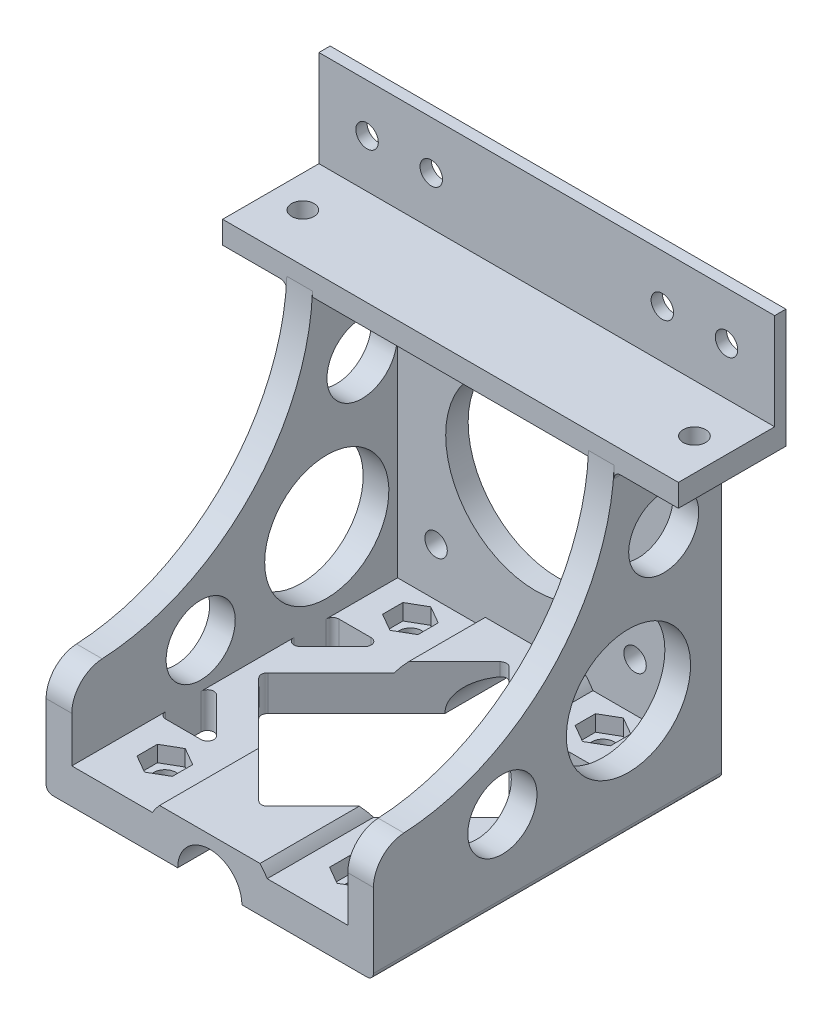
SolidWorks part; units mm, degrees
ref_plane "Front Plane" through (0, 0, 0) normal (0, 0, 1) x (1, 0, 0)
ref_plane "Top Plane" through (0, 0, 0) normal (0, 1, 0) x (1, 0, 0)
ref_plane "Right Plane" through (0, 0, 0) normal (1, 0, 0) x (0, 0, -1)
sketch "Sketch1" plane through (0, 0, 0) normal (0, 0, 1) x (1, 0, 0)
  line L1 (-51.9324, 28.7717) -> (-0.9324, 28.7717)
  line L2 (-51.9324, 28.7717) -> (-51.9324, -24.7283)
  line L3 (-51.9324, -24.7283) -> (-0.9324, -24.7283)
  line L4 (-0.9324, 28.7717) -> (-0.9324, -24.7283)
  dimension "D1" = 51
  dimension "D2" = 53.5
extrude "Boss-Extrude1" add sketch "Sketch1" along normal blind 54.25
sketch "Sketch2" plane through (0, 0, 54.25) normal (0, 0, 1) x (1, 0, 0)
  line L0 (-0.9324, -24.7283) -> (-0.9324, 28.7717) construction
  line L1 (-47.9324, -17.7283) -> (-4.9324, -17.7283)
  line L2 (-47.9324, -17.7283) -> (-47.9324, 25.2717)
  line L3 (-47.9324, 25.2717) -> (-4.9324, 25.2717)
  line L4 (-4.9324, -17.7283) -> (-4.9324, 25.2717)
  line L6 (-51.9324, -24.7283) -> (-0.9324, -24.7283) construction
  dimension "D1" = 43
  dimension "D2" = 43
  dimension "D3" = 4
  dimension "D4" = 7
extrude "Cut-Extrude1" cut sketch "Sketch2" against normal offset from surface (50.75 mm away) 3.5 up to face at (-26.4324, 2.0217, 0)
sketch "Sketch3" plane through (0, 0, 54.25) normal (0, 0, 1) x (1, 0, 0)
  line L0 (-0.9324, 28.7717) -> (-51.9324, 28.7717) construction
  line L1 (-47.9324, 25.2717) -> (-4.9324, 25.2717)
  line L2 (-47.9324, 25.2717) -> (-47.9324, 28.7717)
  line L3 (-47.9324, 28.7717) -> (-4.9324, 28.7717)
  line L4 (-4.9324, 25.2717) -> (-4.9324, 28.7717)
extrude "Cut-Extrude2" cut sketch "Sketch3" against normal offset from surface (37.5 mm away) 16.75 up to face at (-26.4324, 2.0217, 0)
sketch "Sketch4" plane through (-51.9324, 0, 0) normal (-1, 0, 0) x (0, 0, 1)
  line L0 (16.75, 25.2717) -> (16.75, 28.7717) construction
  line L1 (54.25, 28.7717) -> (54.25, -24.7283) construction
  line L3 (16.75, 28.7717) -> (54.25, 28.7717)
  line L4 (54.25, 28.7717) -> (54.25, -7.0747)
  arc A0 (16.75, 28.7717) -> (54.25, -7.0747) centre (51.3457, 27.4252) ccw
extrude "Cut-Extrude3" cut sketch "Sketch4" against normal blind 76
sketch "Sketch5" plane through (-51.9324, 0, 0) normal (-1, 0, 0) x (0, 0, 1)
  circle A0 centre (14.5252, -6.808) radius 9.6731
  circle A1 centre (34.169, -12.2977) radius 5.3908
  circle A2 centre (9.0356, 13.1664) radius 5.4569
extrude "Cut-Extrude4" cut sketch "Sketch5" against normal blind 76
sketch "Sketch6" plane through (0, 0, 3.5) normal (0, 0, 1) x (1, 0, 0)
  line L0 (-4.9324, 25.2717) -> (-47.9324, -17.7283) construction
  line L1 (-4.9324, -17.7283) -> (-47.9324, 25.2717) construction
  circle A0 centre (-26.4324, 3.7717) radius 14
  circle A1 centre (-10.9324, 19.2717) radius 1.75
  circle A2 centre (-41.9324, 19.2717) radius 1.75
  circle A3 centre (-41.9324, -11.7283) radius 1.75
  circle A4 centre (-10.9324, -11.7283) radius 1.75
  dimension "D2" = 28
  dimension "D3" = 3.5
  dimension "D1" = 31
extrude "Cut-Extrude5" cut sketch "Sketch6" against normal blind 76
sketch "Sketch7" plane through (0, 0, 0) normal (0, 0, -1) x (-1, 0, 0)
  line L0 (51.9324, -24.7283) -> (0.9324, -24.7283) construction
  circle A0 centre (26.4324, -24.7283) radius 5
  dimension "D1" = 10
extrude "Cut-Extrude6" cut sketch "Sketch7" against normal blind 76
sketch "Sketch8" plane through (0, -24.7283, 0) normal (0, -1, 0) x (1, 0, 0)
  line L0 (-26.4324, 54.25) -> (-26.4324, 0) construction
  line L1 (-21.4324, 54.25) -> (-31.4324, 54.25) construction
  line L2 (-31.4324, 0) -> (-21.4324, 0) construction
  line L3 (-26.4324, 46.625) -> (-6.9324, 27.125)
  line L4 (-4.9324, 3.5) -> (-4.9324, 54.25) construction
  line L5 (-6.9324, 27.125) -> (-26.4324, 7.625)
  line L7 (-26.4324, 7.625) -> (-45.9324, 27.125)
  line L8 (-45.9324, 27.125) -> (-26.4324, 46.625)
  line L9 (-47.9324, 3.5) -> (-47.9324, 54.25) construction
  line L10 (-26.4324, 7.625) -> (-4.9324, 7.625) construction
  line L11 (-26.4324, 7.625) -> (-47.9324, 7.625) construction
  line L12 (-26.4324, 46.625) -> (-47.9324, 46.625) construction
  line L13 (-26.4324, 46.625) -> (-4.9324, 46.625) construction
  line L14 (-13.3613, 40.625) -> (-4.9324, 40.625)
  line L15 (-4.9324, 40.625) -> (-4.9324, 32.1961)
  line L16 (-4.9324, 32.1961) -> (-13.3613, 40.625)
  line L17 (-4.9324, 13.625) -> (-13.3613, 13.625)
  line L18 (-13.3613, 13.625) -> (-4.9324, 22.0539)
  line L19 (-4.9324, 22.0539) -> (-4.9324, 13.625)
  line L20 (-47.9324, 13.625) -> (-39.5034, 13.625)
  line L21 (-39.5034, 13.625) -> (-47.9324, 22.0539)
  line L22 (-47.9324, 22.0539) -> (-47.9324, 13.625)
  line L23 (-47.9324, 40.625) -> (-39.0071, 40.625)
  line L24 (-39.0071, 40.625) -> (-47.9324, 31.6997)
  line L25 (-47.9324, 31.6997) -> (-47.9324, 40.625)
  line L26 (-6.9324, 0) -> (-6.9324, 54.25) construction
  line L27 (-21.4324, 0) -> (-0.9324, 0) construction
  line L28 (-21.4324, 54.25) -> (-0.9324, 54.25) construction
  line L29 (-45.9324, 54.25) -> (-45.9324, 0) construction
  line L30 (-51.9324, 54.25) -> (-31.4324, 54.25) construction
  line L31 (-51.9324, 0) -> (-31.4324, 0) construction
  line L32 (-0.9324, 54.25) -> (-0.9324, 0) construction
  dimension "D1" = 7.625
  dimension "D2" = 45
  dimension "D3" = 6
  dimension "D4" = 45
  dimension "D5" = 5
  dimension "D6" = 6
  dimension "D7" = 5
  dimension "D8" = 5
  dimension "D9" = 6
extrude "Cut-Extrude7" cut sketch "Sketch8" against normal blind 27
fillet "Fillet2" radius 1 16 edges at (-47.9324, -21.2283, 31.6997) (-4.9324, -21.2283, 32.1961) (-4.9324, -21.2283, 22.0539) (-47.9324, -21.2283, 22.0539) (-13.3613, -21.2283, 13.625) (-39.5034, -21.2283, 13.625) (-26.4324, -18.7283, 7.625) (-4.9324, -21.2283, 13.625) (-47.9324, -21.2283, 13.625) (-45.9324, -21.2283, 27.125) (-6.9324, -21.2283, 27.125) (-4.9324, -21.2283, 40.625) (-47.9324, -21.2283, 40.625) (-39.0071, -21.2283, 40.625) (-13.3613, -21.2283, 40.625) (-26.4324, -18.7283, 46.625)
sketch "Sketch12" plane through (0, -24.7283, 0) normal (0, -1, 0) x (1, 0, 0)
  line L1 (-47.9324, 54.25) -> (-4.9324, 54.25) construction
  line L2 (-21.4324, 54.25) -> (-31.4324, 54.25) construction
  line L4 (-10.9471, 13.625) -> (-5.9324, 13.625) construction
  line L5 (-5.9324, 40.625) -> (-10.9471, 40.625) construction
  circle A0 centre (-11.4324, 46.25) radius 1.75
  circle A1 centre (-41.4324, 46.25) radius 1.75
  circle A2 centre (-11.4324, 8) radius 1.75
  circle A3 centre (-41.4324, 8) radius 1.75
  point P10 (-26.4324, 54.25)
  point P13 (-26.4324, 54.25)
  dimension "D1" = 5.625
  dimension "D2" = 15
  dimension "D3" = 15
  dimension "D4" = 5.625
extrude "Cut-Extrude8" cut sketch "Sketch12" against normal blind 15
sketch "Sketch13" plane through (-51.9324, 0, 0) normal (-1, 0, 0) x (0, 0, 1)
  line L0 (3.5, 25.2717) -> (16.75, 25.2717) construction
  line L1 (0, 28.7717) -> (16.75, 28.7717)
  line L2 (0, 28.7717) -> (0, 25.2717)
  line L3 (0, 25.2717) -> (16.75, 25.2717)
  line L4 (16.75, 28.7717) -> (16.75, 25.2717)
  line L5 (16.75, 28.7717) -> (0, 28.7717) construction
  arc A0 (16.75, 28.7717) -> (54.25, -7.0747) centre (51.3457, 27.4252) ccw construction
extrude "Boss-Extrude4" add sketch "Sketch13" along normal blind 10 and the other way offset from surface (61 mm away) 10 other way up to face at (-0.9324, 7.7095, 9.0356)
sketch "Sketch14" plane through (0, 28.7717, 0) normal (0, 1, 0) x (1, 0, 0)
  line L0 (9.0676, 0) -> (9.0676, -16.75) construction
  line L1 (-61.9324, 0) -> (9.0676, 0)
  line L2 (-61.9324, 0) -> (-61.9324, -1.75)
  line L3 (-61.9324, -1.75) -> (9.0676, -1.75)
  line L4 (9.0676, 0) -> (9.0676, -1.75)
  dimension "D1" = 1.75
extrude "Boss-Extrude5" add sketch "Sketch14" along normal blind 15
sketch "Sketch15" plane through (0, 25.2717, 0) normal (0, -1, 0) x (1, 0, 0)
  line L0 (4.0676, 0) -> (4.0676, 16.75) construction
  line L1 (9.0676, 0) -> (-0.9324, 0) construction
  line L2 (9.0676, 16.75) -> (-0.9324, 16.75) construction
  line L3 (9.0676, 9.25) -> (-61.9324, 9.25) construction
  line L6 (-56.9324, 16.75) -> (-56.9324, 0) construction
  line L7 (-51.9324, 16.75) -> (-61.9324, 16.75) construction
  line L8 (-51.9324, 0) -> (-61.9324, 0) construction
  circle A0 centre (-56.9324, 9.25) radius 1.75
  circle A1 centre (4.0676, 9.25) radius 1.75
  dimension "D1" = 3.5
  dimension "D2" = 7.5
extrude "Cut-Extrude9" cut sketch "Sketch15" against normal blind 10
sketch "Sketch16" plane through (0, 0, 0) normal (0, 0, -1) x (-1, 0, 0)
  line L0 (-9.0676, 43.7717) -> (61.9324, 43.7717) construction
  line L1 (61.9324, 43.7717) -> (61.9324, 25.2717) construction
  line L2 (-9.0676, 25.2717) -> (-9.0676, 43.7717) construction
  circle A0 centre (54.4324, 36.2717) radius 1.75
  circle A1 centre (-1.5676, 36.2717) radius 1.75
  circle A2 centre (44.4324, 36.2717) radius 1.75
  circle A3 centre (8.4324, 36.2717) radius 1.75
  dimension "D1" = 3.5
  dimension "D2" = 7.5
  dimension "D3" = 7.5
  dimension "D4" = 7.5
  dimension "D5" = 10
  dimension "D6" = 10
  dimension "D7" = 7.5
  dimension "D8" = 7.5
extrude "Cut-Extrude10" cut sketch "Sketch16" against normal blind 10
sketch "Sketch17" plane through (0, 0, 54.25) normal (0, 0, 1) x (1, 0, 0)
  line L0 (-17.4881, -19.2283) -> (-4.9324, -19.2283)
  line L2 (-4.9324, -24.7283) -> (-4.9324, -17.7283) construction
  line L3 (-4.9324, -19.2283) -> (-4.9324, -17.7283)
  line L5 (-4.9324, -17.7283) -> (-18.6061, -17.7283)
  line L7 (-47.9324, -17.7283) -> (-4.9324, -17.7283) construction
  line L8 (-35.3766, -19.2283) -> (-47.9324, -19.2283)
  line L10 (-47.9324, -17.7283) -> (-47.9324, -24.7283) construction
  line L11 (-47.9324, -19.2283) -> (-47.9324, -17.7283)
  line L12 (-47.9324, -17.7283) -> (-34.2586, -17.7283)
  line L13 (-21.4324, -24.7283) -> (-0.9324, -24.7283) construction
  arc A0 (-17.4881, -19.2283) -> (-18.6061, -17.7283) centre (-26.4324, -24.7283) ccw
  arc A1 (-34.2586, -17.7283) -> (-35.3766, -19.2283) centre (-26.4324, -24.7283) ccw
  dimension "D1" = 21
  dimension "D2" = 5.5
extrude "Cut-Extrude11" cut sketch "Sketch17" against normal up to surface (50.75 mm away) up to face at (-9.1824, -11.7283, 3.5)
fillet "Fillet3" radius 5 2 edges at (-49.9324, -7.0747, 54.25) (-2.9324, -7.0747, 54.25)
fillet "Fillet4" radius 1 4 edges at (-0.9324, 25.2717, 8.375) (-51.9324, 25.2717, 8.375) (-0.9324, -24.7283, 27.125) (-51.9324, -24.7283, 27.125)
sketch "Sketch19" plane through (0, -19.2283, 0) normal (0, 1, 0) x (1, 0, 0)
  line L0 (-4.9324, -16.75) -> (-4.9324, -49.5145) construction
  line L1 (-44.1824, -9.5877) -> (-41.4324, -11.1754)
  line L2 (-41.4324, -11.1754) -> (-38.6824, -9.5877)
  line L3 (-38.6824, -9.5877) -> (-38.6824, -6.4123)
  line L4 (-38.6824, -6.4123) -> (-41.4324, -4.8246)
  line L5 (-41.4324, -4.8246) -> (-44.1824, -6.4123)
  line L6 (-44.1824, -6.4123) -> (-44.1824, -9.5877)
  line L7 (-11.4324, -4.8246) -> (-14.1824, -6.4123)
  line L8 (-14.1824, -6.4123) -> (-14.1824, -9.5877)
  line L9 (-14.1824, -9.5877) -> (-11.4324, -11.1754)
  line L10 (-11.4324, -11.1754) -> (-8.6824, -9.5877)
  line L11 (-8.6824, -9.5877) -> (-8.6824, -6.4123)
  line L12 (-8.6824, -6.4123) -> (-11.4324, -4.8246)
  line L13 (-38.6824, -47.8377) -> (-38.6824, -44.6623)
  line L14 (-38.6824, -44.6623) -> (-41.4324, -43.0746)
  line L15 (-41.4324, -43.0746) -> (-44.1824, -44.6623)
  line L16 (-44.1824, -44.6623) -> (-44.1824, -47.8377)
  line L17 (-44.1824, -47.8377) -> (-41.4324, -49.4254)
  line L18 (-41.4324, -49.4254) -> (-38.6824, -47.8377)
  line L19 (-8.6824, -47.8377) -> (-8.6824, -44.6623)
  line L20 (-8.6824, -44.6623) -> (-11.4324, -43.0746)
  line L21 (-11.4324, -43.0746) -> (-14.1824, -44.6623)
  line L22 (-14.1824, -44.6623) -> (-14.1824, -47.8377)
  line L23 (-14.1824, -47.8377) -> (-11.4324, -49.4254)
  line L24 (-11.4324, -49.4254) -> (-8.6824, -47.8377)
  circle A0 centre (-41.4324, -8) radius 2.75 construction
  circle A1 centre (-11.4324, -8) radius 2.75 construction
  circle A2 centre (-41.4324, -46.25) radius 2.75 construction
  circle A3 centre (-11.4324, -46.25) radius 2.75 construction
  dimension "D1" = 5.5
extrude "Cut-Extrude12" cut sketch "Sketch19" against normal blind 2.5
